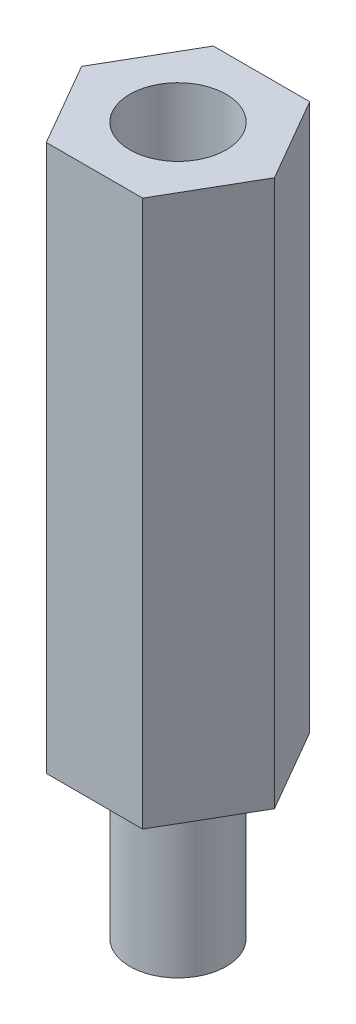
SolidWorks part; units mm, degrees
ref_plane "Front Plane" through (0, 0, 0) normal (0, 0, 1) x (1, 0, 0)
ref_plane "Top Plane" through (0, 0, 0) normal (0, 1, 0) x (1, 0, 0)
ref_plane "Right Plane" through (0, 0, 0) normal (1, 0, 0) x (0, 0, -1)
sketch "Sketch1" plane through (0, 0, 0) normal (0, 1, 0) x (1, 0, 0)
  line L1 (3, 0) -> (1.5, 2.5981)
  line L2 (1.5, 2.5981) -> (-1.5, 2.5981)
  line L3 (-1.5, 2.5981) -> (-3, 0)
  line L4 (-3, 0) -> (-1.5, -2.5981)
  line L5 (-1.5, -2.5981) -> (1.5, -2.5981)
  line L6 (1.5, -2.5981) -> (3, 0)
  circle A0 centre (0, 0) radius 2.5981 construction
  circle A1 centre (0, 0) radius 1.5
  dimension "D2" = 3
  dimension "D1" = 3
extrude "Boss-Extrude1" add sketch "Sketch1" along normal blind 15
sketch "Sketch2" plane through (0, 0, 0) normal (0, -1, 0) x (1, 0, 0)
  line L1 (1.5, 2.5981) -> (-1.5, 2.5981)
  line L2 (-1.5, 2.5981) -> (-3, 0)
  line L3 (-3, 0) -> (-1.5, -2.5981)
  line L4 (-1.5, -2.5981) -> (1.5, -2.5981)
  line L5 (1.5, -2.5981) -> (3, 0)
  line L6 (3, 0) -> (1.5, 2.5981)
  circle A0 centre (0, 0) radius 2.5981 construction
extrude "Boss-Extrude2" add sketch "Sketch2" along normal blind 2
sketch "Sketch3" plane through (0, -2, 0) normal (0, -1, 0) x (1, 0, 0)
  circle A0 centre (0, 0) radius 1.5
  dimension "D1" = 3
extrude "Boss-Extrude3" add sketch "Sketch3" along normal blind 5
